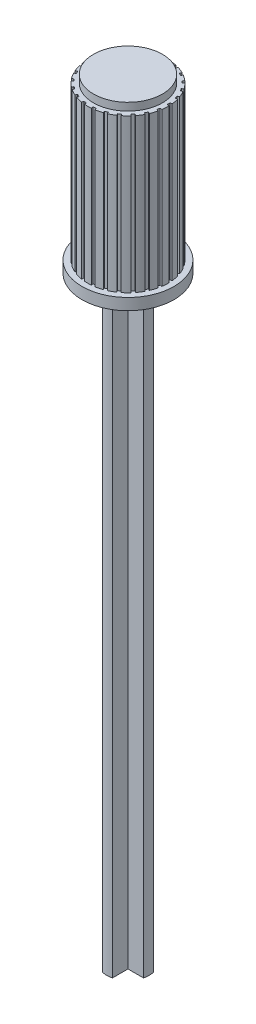
SolidWorks part; units mm, degrees
ref_plane "Front Plane" through (0, 0, 0) normal (0, 0, 1) x (1, 0, 0)
ref_plane "Top Plane" through (0, 0, 0) normal (0, 1, 0) x (1, 0, 0)
ref_plane "Right Plane" through (0, 0, 0) normal (1, 0, 0) x (0, 0, -1)
sketch "Sketch4" plane through (0, 0, 0) normal (0, 1, 0) x (1, 0, 0)
  line L0 (0, 1.375) -> (0, 0) construction
  line L1 (-1.375, 0) -> (0.32, 0) construction
  line L2 (-0.32, 1.3372) -> (-0.32, 0.32)
  line L3 (-1.3372, -0.32) -> (-0.32, -0.32)
  line L4 (0.32, 1.3372) -> (0.32, 0.32)
  line L5 (-1.3372, 0.32) -> (-0.32, 0.32)
  line L6 (0.32, 0.32) -> (1.3372, 0.32)
  line L7 (-1.375, 0.32) -> (1.375, 0.32) construction
  line L8 (0.32, -0.32) -> (1.3372, -0.32)
  line L9 (-1.375, -0.32) -> (1.375, -0.32) construction
  line L10 (-0.32, -0.32) -> (-0.32, -1.3372)
  line L11 (-0.32, 1.375) -> (-0.32, -1.375) construction
  line L12 (0, 1.375) -> (0, -1.375) construction
  line L13 (0.32, -0.32) -> (0.32, -1.3372)
  line L14 (0.32, 1.375) -> (0.32, -1.375) construction
  line L15 (-1.375, 0) -> (1.375, 0) construction
  arc A0 (-1.3372, 0.32) -> (-1.3372, -0.32) centre (0, 0) ccw
  arc A1 (0.32, 1.3372) -> (-0.32, 1.3372) centre (0, 0) ccw
  arc A2 (1.3372, -0.32) -> (1.3372, 0.32) centre (0, 0) ccw
  arc A3 (-0.32, -1.3372) -> (0.32, -1.3372) centre (0, 0) ccw
  dimension "D1" = 2.75
  dimension "D2" = 0.32
  dimension "D3" = 0.32
extrude "Boss-Extrude2" add sketch "Sketch4" along normal blind 39
sketch "Sketch5" plane through (0, 39, 0) normal (0, 1, 0) x (1, 0, 0)
  circle A0 centre (0, 0) radius 3
  dimension "D1" = 6
extrude "Boss-Extrude3" add sketch "Sketch5" along normal blind 0.75
sketch "Sketch9" plane through (0, 39.75, 0) normal (0, 1, 0) x (1, 0, 0)
  line L0 (-0.8304, -2.3581) -> (-0.8732, -2.4796)
  line L3 (-0.2179, -2.4905) -> (-0.2291, -2.6189)
  line L4 (0.2179, -2.4905) -> (0.2291, -2.6189)
  line L5 (-0.4083, -2.4664) -> (-0.4294, -2.5936)
  line L6 (-1.3907, -2.0775) -> (-1.4624, -2.1845)
  line L7 (-1.0089, -2.2874) -> (-1.0609, -2.4053)
  line L8 (-1.8637, -1.6663) -> (-1.9598, -1.7522)
  line L9 (-1.546, -1.9646) -> (-1.6257, -2.0659)
  line L10 (-2.2195, -1.1505) -> (-2.3339, -1.2098)
  line L11 (-1.986, -1.5184) -> (-2.0884, -1.5967)
  line L12 (-2.4359, -0.5624) -> (-2.5615, -0.5914)
  line L13 (-2.3013, -0.9768) -> (-2.4199, -1.0272)
  line L14 (-2.4993, 0.0611) -> (-2.6281, 0.0642)
  line L15 (-2.4719, -0.3738) -> (-2.5993, -0.3931)
  line L16 (-2.4055, 0.6807) -> (-2.5295, 0.7158)
  line L17 (-2.4872, 0.2526) -> (-2.6154, 0.2657)
  line L18 (-2.1607, 1.2575) -> (-2.2721, 1.3224)
  line L19 (-2.3462, 0.8632) -> (-2.4672, 0.9077)
  line L20 (-1.7801, 1.7554) -> (-1.8718, 1.8459)
  line L21 (-2.0578, 1.4196) -> (-2.1639, 1.4928)
  line L22 (-1.2876, 2.1429) -> (-1.354, 2.2534)
  line L23 (-1.6401, 1.8868) -> (-1.7247, 1.984)
  line L24 (-0.7142, 2.3958) -> (-0.751, 2.5193)
  line L25 (-1.1194, 2.2354) -> (-1.1771, 2.3506)
  line L26 (-0.096, 2.4982) -> (-0.1009, 2.6269)
  line L27 (-0.5283, 2.4435) -> (-0.5555, 2.5695)
  line L28 (0.5283, 2.4435) -> (0.5555, 2.5695)
  line L29 (0.096, 2.4982) -> (0.1009, 2.6269)
  line L30 (1.1194, 2.2354) -> (1.1771, 2.3506)
  line L31 (0.7142, 2.3958) -> (0.751, 2.5193)
  line L32 (1.6401, 1.8868) -> (1.7247, 1.984)
  line L33 (1.2876, 2.1429) -> (1.354, 2.2534)
  line L34 (2.0578, 1.4196) -> (2.1639, 1.4928)
  line L35 (1.7801, 1.7554) -> (1.8718, 1.8459)
  line L36 (2.3462, 0.8632) -> (2.4672, 0.9077)
  line L37 (2.1607, 1.2575) -> (2.2721, 1.3224)
  line L38 (2.4872, 0.2526) -> (2.6154, 0.2657)
  line L39 (2.4055, 0.6807) -> (2.5295, 0.7158)
  line L40 (2.4719, -0.3738) -> (2.5993, -0.3931)
  line L41 (2.4993, 0.0611) -> (2.6281, 0.0642)
  line L42 (2.3013, -0.9768) -> (2.4199, -1.0272)
  line L43 (2.4359, -0.5624) -> (2.5615, -0.5914)
  line L44 (1.986, -1.5184) -> (2.0884, -1.5967)
  line L45 (2.2195, -1.1505) -> (2.3339, -1.2098)
  line L46 (1.546, -1.9646) -> (1.6257, -2.0659)
  line L47 (1.8637, -1.6663) -> (1.9598, -1.7522)
  line L48 (1.0089, -2.2874) -> (1.0609, -2.4053)
  line L49 (1.3907, -2.0775) -> (1.4624, -2.1845)
  line L50 (0.4083, -2.4664) -> (0.4294, -2.5936)
  line L51 (0.8304, -2.3581) -> (0.8732, -2.4796)
  arc A0 (0.2179, -2.4905) -> (0.4083, -2.4664) centre (0, 0) ccw
  arc A4 (-0.2291, -2.6189) -> (0.2291, -2.6189) centre (0, 0) ccw
  arc A5 (-0.8732, -2.4796) -> (-0.4294, -2.5936) centre (0, 0) ccw
  arc A6 (-1.4624, -2.1845) -> (-1.0609, -2.4053) centre (0, 0) ccw
  arc A7 (-1.9598, -1.7522) -> (-1.6257, -2.0659) centre (0, 0) ccw
  arc A8 (-2.3339, -1.2098) -> (-2.0884, -1.5967) centre (0, 0) ccw
  arc A9 (-2.5615, -0.5914) -> (-2.4199, -1.0272) centre (0, 0) ccw
  arc A10 (-2.6281, 0.0642) -> (-2.5993, -0.3931) centre (0, 0) ccw
  arc A11 (-2.5295, 0.7158) -> (-2.6154, 0.2657) centre (0, 0) ccw
  arc A12 (-2.2721, 1.3224) -> (-2.4672, 0.9077) centre (0, 0) ccw
  arc A13 (-1.8718, 1.8459) -> (-2.1639, 1.4928) centre (0, 0) ccw
  arc A14 (-1.354, 2.2534) -> (-1.7247, 1.984) centre (0, 0) ccw
  arc A15 (-0.751, 2.5193) -> (-1.1771, 2.3506) centre (0, 0) ccw
  arc A16 (-0.1009, 2.6269) -> (-0.5555, 2.5695) centre (0, 0) ccw
  arc A17 (0.5555, 2.5695) -> (0.1009, 2.6269) centre (0, 0) ccw
  arc A18 (1.1771, 2.3506) -> (0.751, 2.5193) centre (0, 0) ccw
  arc A19 (1.7247, 1.984) -> (1.354, 2.2534) centre (0, 0) ccw
  arc A20 (2.1639, 1.4928) -> (1.8718, 1.8459) centre (0, 0) ccw
  arc A21 (2.4672, 0.9077) -> (2.2721, 1.3224) centre (0, 0) ccw
  arc A22 (2.6154, 0.2657) -> (2.5295, 0.7158) centre (0, 0) ccw
  arc A23 (2.5993, -0.3931) -> (2.6281, 0.0642) centre (0, 0) ccw
  arc A24 (2.4199, -1.0272) -> (2.5615, -0.5914) centre (0, 0) ccw
  arc A25 (2.0884, -1.5967) -> (2.3339, -1.2098) centre (0, 0) ccw
  arc A26 (1.6257, -2.0659) -> (1.9598, -1.7522) centre (0, 0) ccw
  arc A27 (1.0609, -2.4053) -> (1.4624, -2.1845) centre (0, 0) ccw
  arc A28 (0.4294, -2.5936) -> (0.8732, -2.4796) centre (0, 0) ccw
  arc A29 (-1.546, -1.9646) -> (-1.3907, -2.0775) centre (0, 0) ccw
  arc A30 (-1.0089, -2.2874) -> (-0.8304, -2.3581) centre (0, 0) ccw
  arc A31 (-0.4083, -2.4664) -> (-0.2179, -2.4905) centre (0, 0) ccw
  arc A32 (0.8304, -2.3581) -> (1.0089, -2.2874) centre (0, 0) ccw
  arc A33 (1.3907, -2.0775) -> (1.546, -1.9646) centre (0, 0) ccw
  arc A34 (1.8637, -1.6663) -> (1.986, -1.5184) centre (0, 0) ccw
  arc A35 (2.2195, -1.1505) -> (2.3013, -0.9768) centre (0, 0) ccw
  arc A36 (2.4359, -0.5624) -> (2.4719, -0.3738) centre (0, 0) ccw
  arc A37 (2.4993, 0.0611) -> (2.4872, 0.2526) centre (0, 0) ccw
  arc A38 (2.4055, 0.6807) -> (2.3462, 0.8632) centre (0, 0) ccw
  arc A39 (2.1607, 1.2575) -> (2.0578, 1.4196) centre (0, 0) ccw
  arc A40 (1.7801, 1.7554) -> (1.6401, 1.8868) centre (0, 0) ccw
  arc A41 (1.2876, 2.1429) -> (1.1194, 2.2354) centre (0, 0) ccw
  arc A42 (0.7142, 2.3958) -> (0.5283, 2.4435) centre (0, 0) ccw
  arc A43 (0.096, 2.4982) -> (-0.096, 2.4982) centre (0, 0) ccw
  arc A44 (-0.5283, 2.4435) -> (-0.7142, 2.3958) centre (0, 0) ccw
  arc A45 (-1.1194, 2.2354) -> (-1.2876, 2.1429) centre (0, 0) ccw
  arc A46 (-1.6401, 1.8868) -> (-1.7801, 1.7554) centre (0, 0) ccw
  arc A47 (-2.0578, 1.4196) -> (-2.1607, 1.2575) centre (0, 0) ccw
  arc A48 (-2.3462, 0.8632) -> (-2.4055, 0.6807) centre (0, 0) ccw
  arc A49 (-2.4872, 0.2526) -> (-2.4993, 0.0611) centre (0, 0) ccw
  arc A50 (-2.4719, -0.3738) -> (-2.4359, -0.5624) centre (0, 0) ccw
  arc A51 (-2.3013, -0.9768) -> (-2.2195, -1.1505) centre (0, 0) ccw
  arc A52 (-1.986, -1.5184) -> (-1.8637, -1.6663) centre (0, 0) ccw
  point P1 (-0.2235, -2.5547)
  dimension "D1" = 5
  dimension "D2" = 10
  dimension "D3" = 2.6289
  dimension "D4" = 0.1289
  dimension "D5" = 0.1289
  dimension "D6" = 2.5547
  dimension "D7" = 25
extrude "Boss-Extrude5" add sketch "Sketch9" along normal blind 10
sketch "Sketch10" plane through (0, 49.75, 0) normal (0, 1, 0) x (1, 0, 0)
  circle A0 centre (0, 0) radius 2.25
  dimension "D1" = 4.5
extrude "Boss-Extrude6" add sketch "Sketch10" along normal blind 0.5
